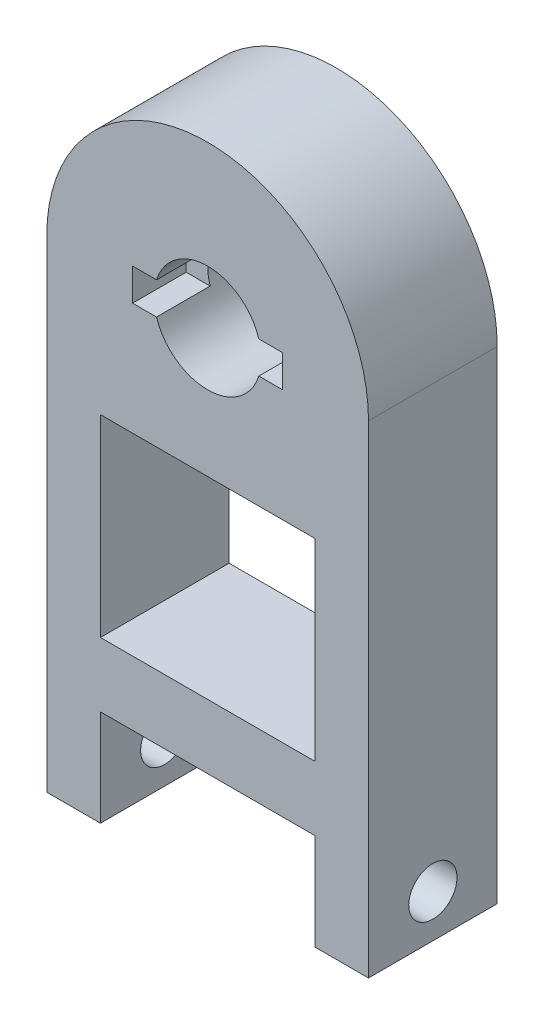
SolidWorks part; units mm, degrees
ref_plane "Front Plane" through (0, 0, 0) normal (0, 0, 1) x (1, 0, 0)
ref_plane "Top Plane" through (0, 0, 0) normal (0, 1, 0) x (1, 0, 0)
ref_plane "Right Plane" through (0, 0, 0) normal (1, 0, 0) x (0, 0, -1)
sketch "Sketch1" plane through (0, 0, 0) normal (0, 0, 1) x (1, 0, 0)
  line L0 (0, 45) -> (0, 9) construction
  line L1 (0, -55) -> (0, 55) construction
  line L2 (15, 45) -> (15, 0)
  line L3 (-15, 45) -> (-15, 0)
  line L4 (55, 0) -> (-55, 0) construction
  line L9 (-15, 0) -> (-10, 0)
  line L10 (-10, 0) -> (-10, 9)
  line L11 (-10, 9) -> (10, 9)
  line L12 (10, 9) -> (10, 0)
  line L13 (0, -32) -> (0, -40) construction
  line L14 (10, 0) -> (15, 0)
  line L16 (-10, 33) -> (10, 33)
  line L17 (-10, 33) -> (-10, 15)
  line L18 (-10, 15) -> (10, 15)
  line L19 (10, 33) -> (10, 15)
  arc A0 (15, 45) -> (-15, 45) centre (0, 45) ccw
  circle A3 centre (0, 45) radius 5
  point P5 (0, 2.5)
  dimension "D3" = 15
  dimension "D4" = 10
  dimension "D1" = 45
  dimension "D2" = 45
  dimension "D7" = 9
  dimension "D8" = 20
  dimension "D9" = 10
  dimension "D10" = 18
  dimension "D11" = 12
extrude "Boss-Extrude1" add sketch "Sketch1" along normal blind 12
sketch "Sketch2" plane through (-15, 0, 0) normal (-1, 0, 0) x (0, 0, 1)
  line L0 (55, 0) -> (-55, 0) construction
  line L1 (0, -55) -> (0, 55) construction
  circle A0 centre (6, 4) radius 2.25
  dimension "D1" = 4
  dimension "D2" = 6
extrude "Cut-Extrude1" cut sketch "Sketch2" against normal through all
sketch "Sketch3" plane through (0, 0, 12) normal (0, 0, 1) x (1, 0, 0)
  line L0 (0, -6.6) -> (0, 6.6) construction
  line L1 (-7, 46.5) -> (7, 46.5)
  line L2 (-7, 46.5) -> (-7, 43.5)
  line L3 (-7, 43.5) -> (7, 43.5)
  line L4 (7, 46.5) -> (7, 43.5)
  arc A0 (15, 45) -> (-15, 45) centre (0, 45) ccw construction
  dimension "D1" = 14
  dimension "D2" = 7
  dimension "D3" = 1.5
  dimension "D4" = 3
extrude "Cut-Extrude2" cut sketch "Sketch3" against normal blind 5
